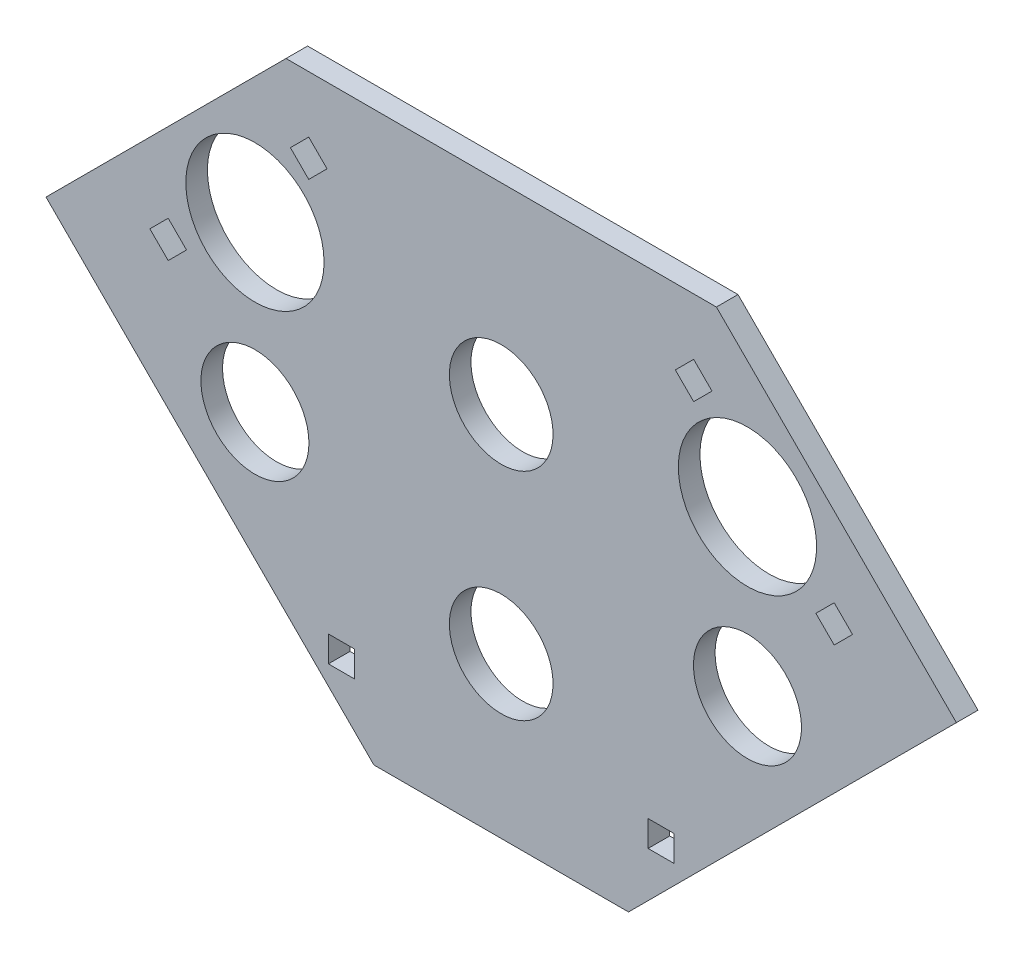
SolidWorks part; units mm, degrees
material "ABS"
ref_plane "Front Plane" through (0, 0, 0) normal (0, 0, 1) x (1, 0, 0)
ref_plane "Top Plane" through (0, 0, 0) normal (0, 1, 0) x (1, 0, 0)
ref_plane "Right Plane" through (0, 0, 0) normal (1, 0, 0) x (0, 0, -1)
sketch "Sketch3" plane through (0, 0, 0) normal (0, 0, 1) x (1, 0, 0)
  line L8 (0, 0) -> (136.4293, 136.4293) construction
  line L9 (0, 0) -> (0, 136.4293) construction
  line L10 (0, 0) -> (-136.4293, 136.4293) construction
  line L20 (-15.2843, -13) -> (15.2843, -13) construction
  line L23 (-15.2843, -13) -> (-77.7817, 49.4975) construction
  line L25 (15.2843, -13) -> (77.7817, 49.4975) construction
  line L27 (-77.7817, 49.4975) -> (-49.4975, 77.7817)
  line L29 (49.4975, 77.7817) -> (77.7817, 49.4975)
  line L32 (-15.2843, -13) -> (15.2843, -13) construction
  line L34 (-27.4975, -22) -> (27.4975, -22)
  line L36 (-27.4975, -22) -> (-88.3883, 38.8909)
  line L37 (-88.3883, 38.8909) -> (-77.7817, 49.4975)
  line L42 (-49.4975, 77.7817) -> (-40.0115, 68.2957) construction
  line L47 (27.4975, -22) -> (88.3883, 38.8909)
  line L48 (88.3883, 38.8909) -> (77.7817, 49.4975)
  line L49 (0, 0) -> (0, -22) construction
  line L50 (-49.4975, 77.7817) -> (-43.8406, 83.4386)
  line L51 (-43.8406, 83.4386) -> (43.8406, 83.4386)
  line L52 (43.8406, 83.4386) -> (49.4975, 77.7817)
  line L53 (49.4975, 77.7817) -> (23.1501, 51.4344) construction
  line L54 (-43.8406, 83.4386) -> (-20.3266, 59.9246) construction
  line L55 (43.8406, 83.4386) -> (35.6049, 75.2028) construction
  line L56 (-81.3173, 44.5477) -> (-77.0746, 48.7904)
  line L57 (-77.0746, 48.7904) -> (-72.832, 44.5477)
  line L58 (-72.832, 44.5477) -> (-77.0746, 40.3051)
  line L59 (-77.0746, 40.3051) -> (-81.3173, 44.5477)
  line L60 (-48.7904, 77.0746) -> (-44.5477, 81.3173)
  line L61 (-44.5477, 81.3173) -> (-40.3051, 77.0746)
  line L62 (-40.3051, 77.0746) -> (-44.5477, 72.832)
  line L63 (-44.5477, 72.832) -> (-48.7904, 77.0746)
  line L64 (40.3051, 77.0746) -> (44.5477, 72.832)
  line L71 (44.5477, 72.832) -> (48.7904, 77.0746)
  line L72 (48.7904, 77.0746) -> (44.5477, 81.3173)
  line L73 (44.5477, 81.3173) -> (40.3051, 77.0746)
  line L74 (72.832, 44.5477) -> (77.0746, 40.3051)
  line L75 (77.0746, 40.3051) -> (81.3173, 44.5477)
  line L76 (81.3173, 44.5477) -> (77.0746, 48.7904)
  line L77 (77.0746, 48.7904) -> (72.832, 44.5477)
  line L82 (0, 0) -> (0, 50) construction
  circle A0 centre (0, 0) radius 12
  circle A1 centre (0, 50) radius 12
  point P7 (63.6396, 63.6396)
  point P15 (-63.6396, 63.6396)
  dimension "crankshaftBearingOD" = 24
  dimension "D22" = 24
  dimension "D8" = 45
  dimension "D10" = 45
  dimension "D2" = 90
  dimension "D3" = 90
  dimension "D4" = 40
  dimension "D5" = 40
  dimension "D6" = 13
  dimension "D7" = 22
  dimension "D9" = 8
  dimension "D11" = 15
  dimension "D15" = 1
  dimension "D16" = 6
  dimension "D18" = 1
  dimension "D19" = 6
  dimension "D12" = 176.7767
  dimension "D13" = 105.4386
  dimension "D17" = 50
extrude "Boss-Extrude1" add sketch "Sketch3" along normal blind 5
sketch "Sketch5" plane through (0, 0, 5) normal (0, 0, 1) x (1, 0, 0)
  line L24 (-43.8406, 83.4386) -> (-88.3883, 38.8909)
  line L25 (-88.3883, 38.8909) -> (-27.4975, -22)
  line L26 (-27.4975, -22) -> (27.4975, -22)
  line L27 (27.4975, -22) -> (88.3883, 38.8909)
  line L28 (88.3883, 38.8909) -> (43.8406, 83.4386)
  line L29 (43.8406, 83.4386) -> (-43.8406, 83.4386)
  line L30 (-43.8406, 83.4386) -> (-88.3883, 38.8909)
  line L31 (-88.3883, 38.8909) -> (-27.4975, -22)
  line L32 (-27.4975, -22) -> (27.4975, -22)
  line L33 (27.4975, -22) -> (88.3883, 38.8909)
  line L34 (88.3883, 38.8909) -> (43.8406, 83.4386)
  line L35 (43.8406, 83.4386) -> (-43.8406, 83.4386)
  line L36 (-105.3589, 38.8909) -> (-49.8112, 94.4386)
  line L37 (-49.8112, 94.4386) -> (49.8112, 94.4386)
  line L38 (49.8112, 94.4386) -> (105.3589, 38.8909)
  line L39 (105.3589, 38.8909) -> (29.468, -37)
  line L40 (29.468, -37) -> (-29.468, -37)
  line L41 (-29.468, -37) -> (-105.3589, 38.8909)
  dimension "D2" = 11
  dimension "D3" = 15
  dimension "D4" = 12
  dimension "D5" = 12
  dimension "D6" = 12
  dimension "D7" = 12
  dimension "D1" = 0
extrude "Boss-Extrude2" add sketch "Sketch5" against normal up to surface (5 mm away) up to face at (-44.5477, 77.0746, 0)
sketch "Sketch6" plane through (0, 0, 5) normal (0, 0, 1) x (1, 0, 0)
  line L0 (-42.468, -24) -> (42.468, -24) construction
  line L1 (-40, -22) -> (-34, -22)
  line L2 (-40, -22) -> (-40, -16)
  line L3 (-40, -16) -> (-34, -16)
  line L4 (-34, -22) -> (-34, -16)
  line L5 (-40, -22) -> (-34, -16) construction
  line L6 (-40, -16) -> (-34, -22) construction
  line L7 (34, -22) -> (40, -22)
  line L8 (34, -22) -> (34, -16)
  line L9 (34, -16) -> (40, -16)
  line L10 (40, -22) -> (40, -16)
  line L11 (34, -22) -> (40, -16) construction
  line L12 (34, -16) -> (40, -22) construction
  line L13 (-105.3589, 38.8909) -> (-29.468, -37) construction
  line L14 (29.468, -37) -> (105.3589, 38.8909) construction
  line L15 (0, 50) -> (0, 0) construction
  line L16 (-48.7904, 77.0746) -> (-77.0746, 48.7904) construction
  line L17 (-77.0746, 48.7904) -> (-62.9325, 62.9325) construction
  line L18 (-62.9325, 62.9325) -> (0, 0) construction
  circle A0 centre (-57, 58) radius 16
  circle A1 centre (-57, 20) radius 12.5
  circle A2 centre (0, 50) radius 40 construction
  circle A3 centre (0, 0) radius 40 construction
  circle A4 centre (57, 20) radius 12.5
  circle A5 centre (57, 58) radius 16
  point P0 (-37, -19)
  point P5 (37, -19)
  dimension "D7" = 25
  dimension "D8" = 57
  dimension "D12" = 80
  dimension "D13" = 32
  dimension "D1" = 6
  dimension "D2" = 24
  dimension "D3" = 2
  dimension "D4" = 2
  dimension "D5" = 37
  dimension "D6" = 37
  dimension "D9" = 8
  dimension "D10" = 57
  dimension "D11" = 20
extrude "Cut-Extrude1" cut sketch "Sketch6" against normal up to surface (5 mm away) up to face at (-44.5477, 77.0746, 0)
equation "\"crankshaftBearingOD@Sketch3\"=24.00mm"
